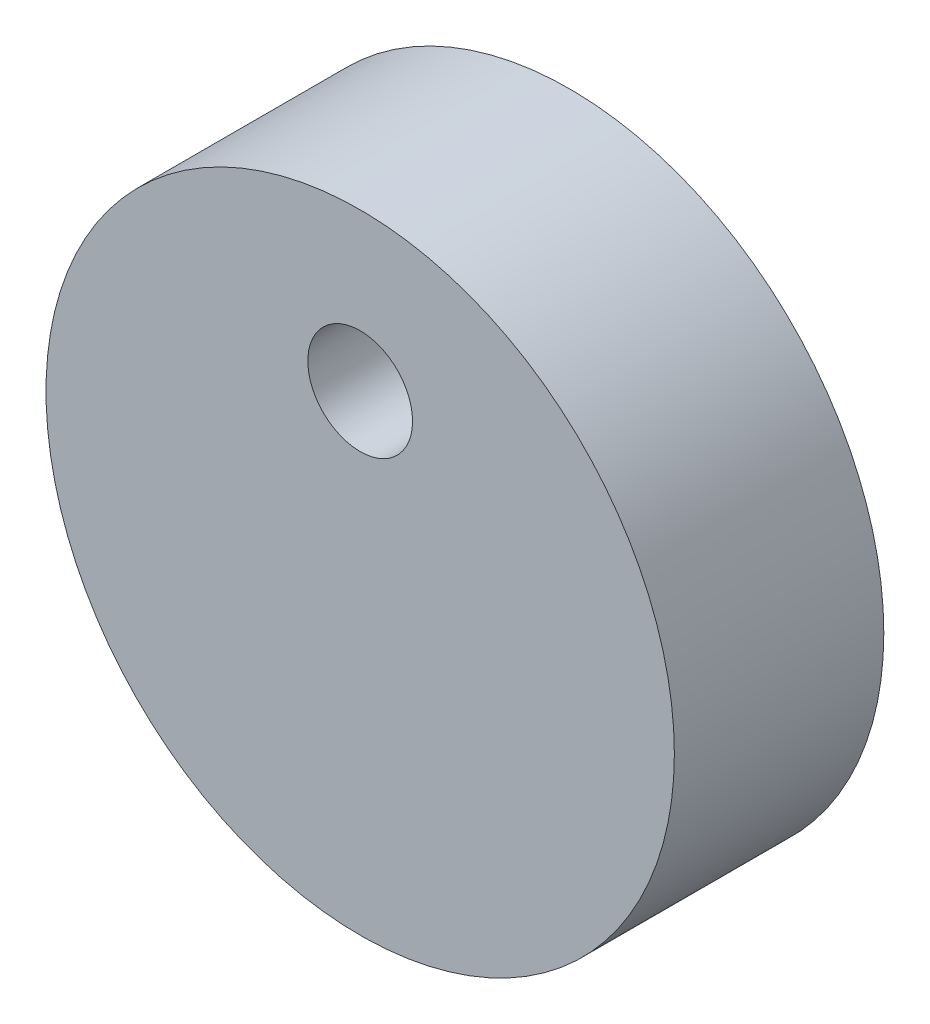
SolidWorks part; units mm, degrees
ref_plane "Front Plane" through (0, 0, 0) normal (0, 0, 1) x (1, 0, 0)
ref_plane "Top Plane" through (0, 0, 0) normal (0, 1, 0) x (1, 0, 0)
ref_plane "Right Plane" through (0, 0, 0) normal (1, 0, 0) x (0, 0, -1)
sketch "Sketch1" plane through (0, 0, 0) normal (0, 0, 1) x (1, 0, 0)
  circle A0 centre (0, 0) radius 38.1
  dimension "D1" = 76.2
extrude "Boss-Extrude1" add sketch "Sketch1" along normal blind 25.4
sketch "Sketch2" plane through (0, 0, 25.4) normal (0, 0, 1) x (1, 0, 0)
  circle A0 centre (0, 19.05) radius 6.35
  dimension "D1" = 12.7
  dimension "D2" = 19.05
extrude "Cut-Extrude1" cut sketch "Sketch2" against normal blind 76.2 contours A0
